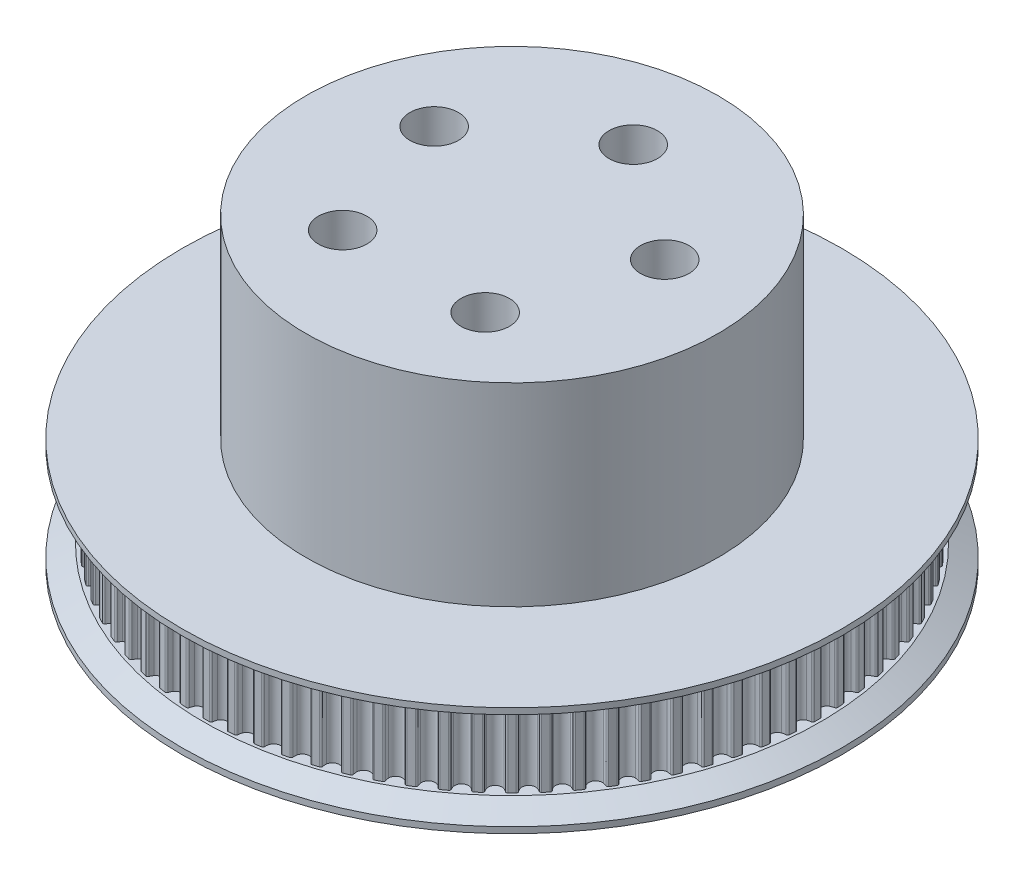
SolidWorks part; units mm, degrees
ref_plane "Front" through (0, 0, 0) normal (0, 0, 1) x (1, 0, 0)
ref_plane "Top" through (0, 0, 0) normal (0, 1, 0) x (1, 0, 0)
ref_plane "Right" through (0, 0, 0) normal (1, 0, 0) x (0, 0, -1)
sketch "Sketch1" plane through (0, 0, 0) normal (0, 1, 0) x (1, 0, 0)
  line L0 (0, 0) -> (0, 25.4648) construction
  line L1 (0, 25.2108) -> (0, 25.8408)
  line L2 (0, 0) -> (0.9997, 25.4452) construction
  line L3 (1.978, 25.1331) -> (2.0274, 25.7611)
  line L4 (1.3894, 25.1757) -> (1.4033, 25.4261) construction
  arc A0 (0.2468, 25.2096) -> (0.3946, 25.0747) centre (0.2453, 25.0596) cw
  arc A1 (0.3946, 25.0747) -> (0.4741, 24.773) centre (1.3894, 25.1757) ccw
  circle A2 centre (0, 0) radius 25.4648 construction
  arc A3 (0.2468, 25.2096) -> (0, 25.2108) centre (0, 0) ccw
  arc A4 (0.9603, 24.4419) -> (0, 24.4608) centre (0, 0) ccw construction
  arc A5 (0.4741, 24.773) -> (1.471, 24.7339) centre (0.9821, 24.9965) ccw
  arc A6 (1.3894, 25.1757) -> (0.9899, 25.1946) centre (0, 0) ccw construction
  arc A7 (0, 25.8408) -> (2.0274, 25.7611) centre (0, 0) cw
  arc A8 (1.574, 25.0284) -> (1.471, 24.7339) centre (0.5901, 25.2071) cw
  arc A9 (1.7319, 25.1512) -> (1.574, 25.0284) centre (1.7216, 25.0016) ccw
  arc A10 (1.7319, 25.1512) -> (1.978, 25.1331) centre (0, 0) cw
  dimension "D1" = 0.15
  dimension "D4" = 50.9296
  dimension "D5" = 1
  dimension "D7" = 0.555
  dimension "D3" = 2.25
  dimension "D8" = 0.75
  dimension "D6" = 0.254
  dimension "D2" = 0.4
  dimension "D9" = 1.38
  dimension "D11" = 0.404
  dimension "D12" = 0.2508
  dimension "D10" = 0.909
sketch "Sketch2" plane through (0, 0, 0) normal (0, 1, 0) x (1, 0, 0)
  circle A0 centre (0, 0) radius 25.4648 construction
  circle A1 centre (0, 0) radius 25.4648
  circle A2 centre (0, 0) radius 6
  dimension "D1" = 12
extrude "Boss-Extrude1" add sketch "Sketch2" along normal mid plane 6
sketch "Sketch6" plane through (0, 0, 0) normal (0, 1, 0) x (1, 0, 0)
  line L0 (0, 25.2008) -> (0, 25.8408)
  line L1 (1.9772, 25.1231) -> (2.0274, 25.7611)
  arc A7 (2.0274, 25.7611) -> (0, 25.8408) centre (0, 0) ccw construction
  arc A8 (2.0274, 25.7611) -> (0, 25.8408) centre (0, 0) ccw
  arc A14 (1.7312, 25.1413) -> (1.5838, 25.0266) centre (1.7216, 25.0016) ccw
  arc A15 (1.4798, 24.7291) -> (1.5838, 25.0266) centre (0.5901, 25.2071) ccw
  arc A16 (0.4649, 24.769) -> (1.4798, 24.7291) centre (0.9821, 24.9965) ccw
  arc A17 (0.3846, 25.0737) -> (0.4649, 24.769) centre (1.3894, 25.1757) ccw
  arc A18 (0.3846, 25.0737) -> (0.2467, 25.1996) centre (0.2453, 25.0596) ccw
  arc A19 (0.2467, 25.1996) -> (0, 25.2008) centre (0, 0) ccw
  arc A20 (1.9772, 25.1231) -> (1.7312, 25.1413) centre (0, 0) ccw
  arc A21 (1.7312, 25.1413) -> (1.5838, 25.0266) centre (1.7216, 25.0016) ccw
  arc A22 (1.4798, 24.7291) -> (1.5838, 25.0266) centre (0.5901, 25.2071) ccw
  arc A23 (0.4649, 24.769) -> (1.4798, 24.7291) centre (0.9821, 24.9965) ccw
  arc A24 (0.3846, 25.0737) -> (0.4649, 24.769) centre (1.3894, 25.1757) ccw
  arc A25 (0.3846, 25.0737) -> (0.2467, 25.1996) centre (0.2453, 25.0596) ccw
  arc A26 (0.2467, 25.1996) -> (0, 25.2008) centre (0, 0) ccw
  arc A27 (1.9772, 25.1231) -> (1.7312, 25.1413) centre (0, 0) ccw
extrude "Cut-Extrude3" cut sketch "Sketch6" against normal through all both and the other way through all
pattern_circular "CirPattern3" count 80 over 360 about axis through (0, 0, 0) along (0, 1, 0) of "Cut-Extrude3"
sketch "Sketch3" plane through (0, 0, 0) normal (0, 0, 1) x (1, 0, 0)
  line L0 (0, 0) -> (0, 9.5108) construction
  line L1 (-25.4648, 3) -> (-27.1968, 4)
  line L2 (-27.1968, 4) -> (-27.1968, 4.5)
  line L3 (-27.1968, 4.5) -> (-6, 4.5)
  line L4 (-6, 4.5) -> (-6, 3)
  line L5 (-6, 3) -> (-25.4648, 3)
  line L6 (6, 3) -> (-6, 3) construction
  dimension "D4" = 50.9296
  dimension "D1" = 1.5
  dimension "D2" = 0.5
  dimension "D3" = 30
revolve "Revolve1" add sketch "Sketch3" angle 360 about L0
mirror "Mirror1" about plane through (0, 0, 0) normal (0, 1, 0) of "Revolve1"
sketch "Sketch4" plane through (0, 0, 0) normal (0, 0, 1) x (1, 0, 0)
  line L0 (0, 0) -> (0, 14.0175) construction
  line L1 (27.1968, 4.5) -> (-27.1968, 4.5) construction
  line L2 (-6, 4.5) -> (-12.5, 4.5)
  line L3 (-6, 4.5) -> (-6, 10.5)
  line L4 (-6, 10.5) -> (-12.5, 10.5)
  line L5 (-12.5, 4.5) -> (-12.5, 10.5)
  dimension "D2" = 6
  dimension "D1" = 6.5
revolve "Revolve2" add sketch "Sketch4" angle 360 about L0
sketch "Sketch5" plane through (0, 0, 0) normal (0, 0, 1) x (1, 0, 0)
  line L1 (0, 4.5) -> (0, 10.5) construction
  line L2 (12.5, 10.5) -> (-12.5, 10.5) construction
  line L7 (-12.5, 10.5) -> (-12.5, 4.5) construction
  line L8 (-12.5, 10.5) -> (-12.5, 4.5) construction
  circle A0 centre (0, 7.5) radius 1.6
  dimension "D1" = 3.2
extrude "Cut-Extrude2" cut sketch "Sketch5" along normal through all
pattern_circular "CirPattern2" count 2 over 90 about axis through (0, 3, 0) along (0, -1, 0) of "Cut-Extrude2"
sketch "Esboço1" plane through (0, -4.5, 0) normal (0, -1, 0) x (1, 0, 0)
  circle A0 centre (0, 0) radius 17
  dimension "D1" = 34
extrude "Ressalto-extrusão1" add sketch "Esboço1" against normal blind 25
sketch "Esboço2" plane through (0, -4.5, 0) normal (0, -1, 0) x (1, 0, 0)
  circle A0 centre (0, -10) radius 2
  circle A1 centre (-9.5106, -3.0902) radius 2
  circle A2 centre (-5.8779, 8.0902) radius 2
  circle A3 centre (5.8779, 8.0902) radius 2
  circle A4 centre (9.5106, -3.0902) radius 2
  point P13 (0, 0)
  dimension "D1" = 4
  dimension "D2" = 10
  dimension "D3" = 5
extrude "Corte-extrusão1" cut sketch "Esboço2" against normal up to surface (25 mm away)
equation "\"belt-step\"= 2"
equation "\"pulley-teeth\"= 80"
equation "\"pulley-dia\"= ( \"belt-step\" * \"pulley-teeth\" ) / Pi"
equation "\"D3@Sketch1\"=(360/\"pulley-teeth\")/2"
equation "\"D4@Sketch1\"=\"pulley-dia\""
equation "\"bore-dia\"= 12"
equation "\"belt-thick\"= 6"
equation "\"D4@Sketch3\"=\"pulley-dia\""
equation "\"D1@Sketch2\"=\"bore-dia\""
equation "\"D1@Boss-Extrude1\"=\"belt-thick\""
equation "\"teeth-offset\"= 0.01"
equation "\"D1@Sketch6\"=\"teeth-offset\""
equation "\"D1@CirPattern3\"=\"pulley-teeth\""
equation "\"flange-wall\"= 6.5"
equation "\"D1@Sketch4\"=\"flange-wall\""
equation "\"flange-h\"= 6"
equation "\"screw-dia\"= 3.2"
equation "\"D2@Sketch4\"=\"flange-h\""
equation "\"D1@Sketch5\"=\"screw-dia\""
equation "\"D10@Sketch1\"=(0.4/(Pi*(\"pulley-dia\"-(2*\"D12@Sketch1\"))))*360"
